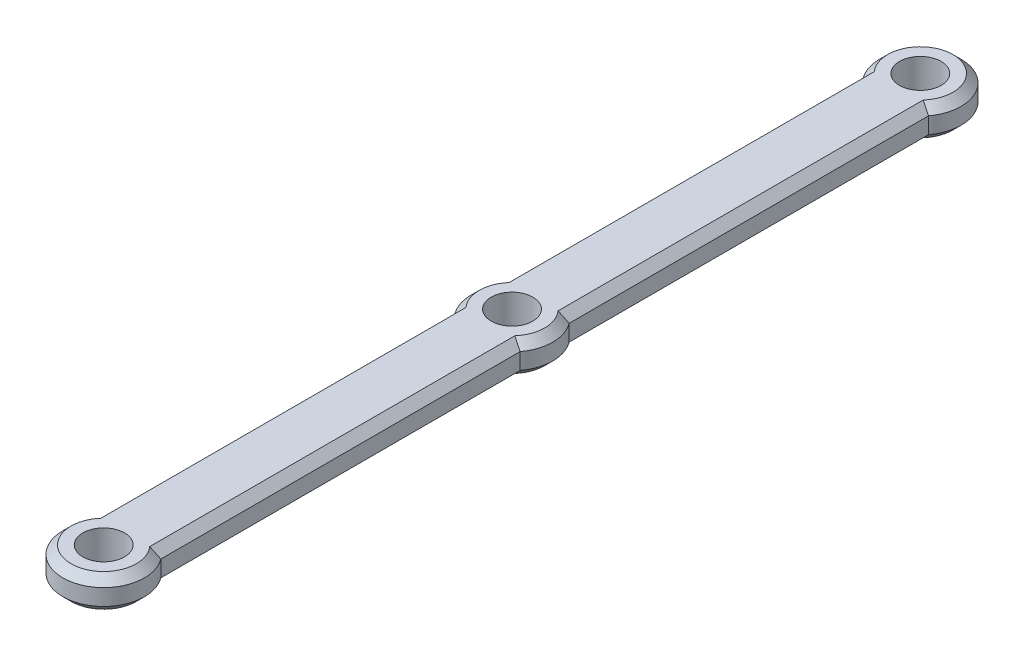
SolidWorks part; units mm, degrees
ref_plane "前视基准面" through (0, 0, 0) normal (0, 0, 1) x (1, 0, 0)
ref_plane "上视基准面" through (0, 0, 0) normal (0, 1, 0) x (1, 0, 0)
ref_plane "右视基准面" through (0, 0, 0) normal (1, 0, 0) x (0, 0, -1)
other "Configuration Table"
sketch "草图1" plane through (0, 0, 0) normal (0, 1, 0) x (1, 0, 0)
  line L0 (0, -50) -> (0, 50) construction
  line L3 (-4, 47) -> (-4, 3)
  line L4 (4, 47) -> (4, 3)
  line L5 (-4, -3) -> (-4, -47)
  line L6 (4, -3) -> (4, -47)
  arc A1 (4, 47) -> (-4, 47) centre (0, 50) ccw
  arc A2 (-4, -47) -> (4, -47) centre (0, -50) ccw
  arc A3 (-4, 3) -> (-4, -3) centre (0, 0) ccw
  arc A4 (4, -3) -> (4, 3) centre (0, 0) ccw
  point P2 (0, 0)
  dimension "D3" = 10
  dimension "D4" = 5
  dimension "D5" = 5
  dimension "D1" = 100
  dimension "D2" = 8
extrude "凸台-拉伸1" add sketch "草图1" along normal blind 4
sketch "草图2" plane through (0, 4, 0) normal (0, 1, 0) x (1, 0, 0)
  line L0 (0, 0) -> (99.318, 0) construction
  circle A0 centre (0, 50) radius 2.55
  circle A1 centre (0, -50) radius 2.55
  circle A2 centre (0, 0) radius 2.55
  dimension "D1" = 5.1
  dimension "D2" = 5.1
extrude "切除-拉伸1" cut sketch "草图2" against normal through all
chamfer "倒角1" distance 1 angle 45 16 edges at (0, 0, -55) (-4, 0, -25) (0, 0, 55) (4, 0, -25) (0, 4, -55) (-4, 4, -25) (0, 4, 55) (4, 4, -25) (5, 0, 0) (4, 0, 25) (-4, 0, 25) (-5, 0, 0) (5, 4, 0) (4, 4, 25) (-4, 4, 25) (-5, 4, 0)
